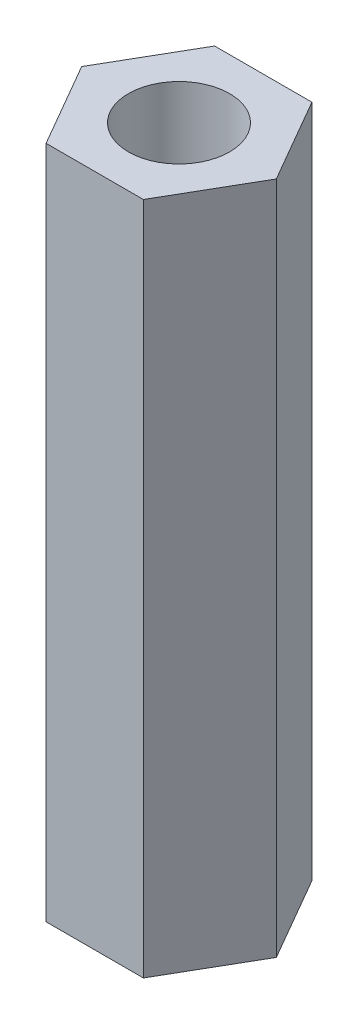
SolidWorks part; units mm, degrees
material "Latón"
ref_plane "Alzado" through (0, 0, 0) normal (0, 0, 1) x (1, 0, 0)
ref_plane "Planta" through (0, 0, 0) normal (0, 1, 0) x (1, 0, 0)
ref_plane "Vista lateral" through (0, 0, 0) normal (1, 0, 0) x (0, 0, -1)
sketch "Croquis1" plane through (0, 0, 0) normal (0, 1, 0) x (1, 0, 0)
  line L1 (1.4434, -2.5) -> (2.8868, 0)
  line L2 (2.8868, 0) -> (1.4434, 2.5)
  line L3 (1.4434, 2.5) -> (-1.4434, 2.5)
  line L4 (-1.4434, 2.5) -> (-2.8868, 0)
  line L5 (-2.8868, 0) -> (-1.4434, -2.5)
  line L6 (-1.4434, -2.5) -> (1.4434, -2.5)
  circle A0 centre (0, 0) radius 2.5 construction
  circle A1 centre (0, 0) radius 1.5
  dimension "D2" = 3
  dimension "D1" = 5
extrude "Saliente-Extruir1" add sketch "Croquis1" along normal mid plane 20
